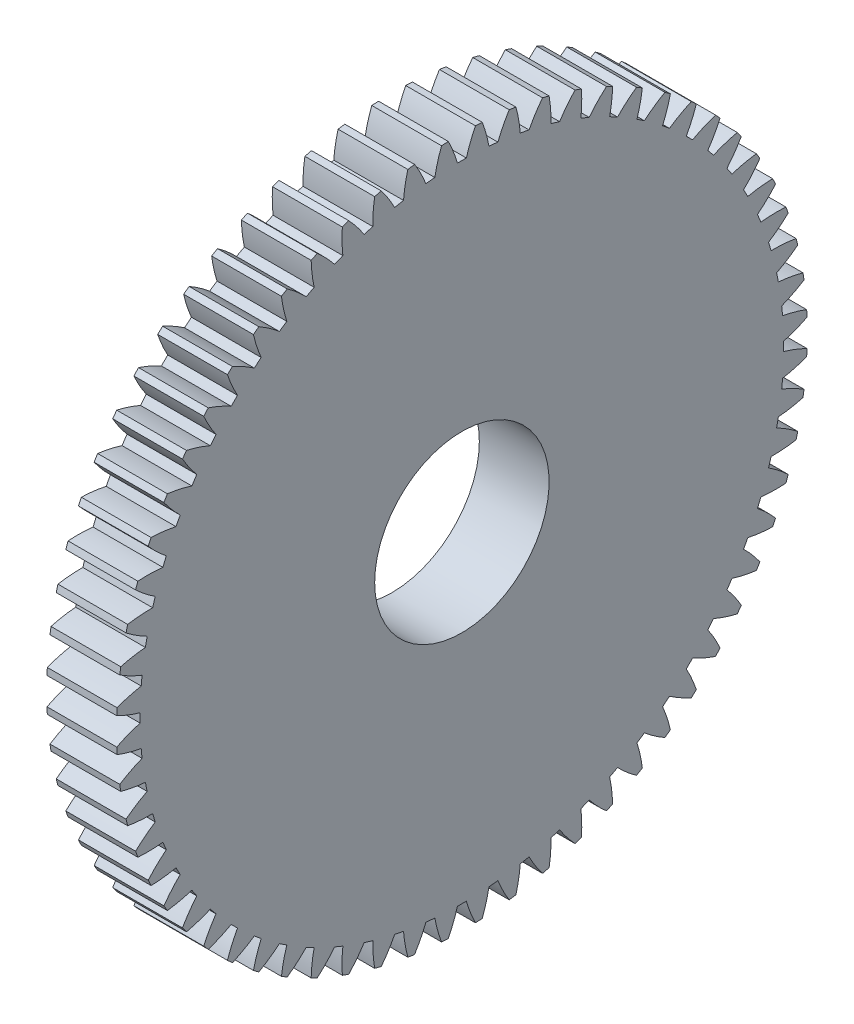
SolidWorks part; units mm, degrees
ref_plane "Plane1" through (0, 0, 0) normal (0, 0, 1) x (1, 0, 0)
ref_plane "Plane2" through (0, 0, 0) normal (0, 1, 0) x (1, 0, 0)
ref_plane "Plane3" through (0, 0, 0) normal (1, 0, 0) x (0, 0, -1)
sketch "HoldingSke" plane through (0, 0, 0) normal (0, 1, 0) x (1, 0, 0)
  line L0 (0, 0) -> (0.7306, -1.498)
  line L1 (-15, 0) -> (100, 0) construction
  line L2 (0, 0) -> (-2.1039, 2.3779)
  line L3 (0, 0) -> (-11.863, 4.5341)
  line L4 (0, 0) -> (3.7858, 7.762)
  line L5 (0, 0) -> (-46.8476, -17.4728)
  line L6 (0, 0) -> (-3.3159, -2.2372)
  line L7 (-2.1039, 2.3779) -> (8.6586, 51.2059)
  line L8 (-76.2, 54.61) -> (-74.4, 54.61)
  line L9 (-71.009, 38.7566) -> (-53.1078, 45.2721)
  line L10 (-76.2, 71.12) -> (104.1128, 71.12)
  line L11 (0, 0) -> (-4, 0)
  line L12 (-76.2, 101.6) -> (-76.177, 101.6)
  line L13 (24.9733, 27.94) -> (52.9518, 28.4284)
  line L14 (24.9733, 27.94) -> (24.9743, 27.94)
  line L15 (24.9733, 27.94) -> (100.4006, 29.5858)
  line L16 (-63.627, -0.6) -> (-12.827, -0.6)
  circle A0 centre (0, 0) radius 5
  circle A1 centre (0, 0) radius 18.449
  circle A2 centre (0, 0) radius 37.5
  circle A3 centre (0, 0) radius 5
  dimension "MHD" = 36.898
  dimension "Hub_dia" = 75
  dimension "Bore" = 10
  dimension "MBD" = 10
  dimension "Num_teeth" = 64
  dimension "Pitch" = 1.6667
  dimension "Overall_len" = 50
  dimension "Show_teeth" = 64
  dimension "Thickness" = 4
  dimension "OAL" = 50.0001
  dimension "T_dim" = 1.8
  dimension "Ap" = 20
  dimension "H" = 19.05
  dimension "Pitch_radius" = 180.3128
  dimension "Width" = 4
  dimension "Backlash" = 0.023
  dimension "Addendum_fac" = 1
  dimension "Dedendum_fac" = 1.25
  dimension "Clearance_fac" = 0.25
  dimension "Dedendum_add" = 0.001
  dimension "Module" = 0.6
sketch "BasProSke" plane through (0, 0, 0) normal (0, 1, 0) x (1, 0, 0)
  line L0 (-10, 0) -> (60, 0) construction
  line L1 (0, 0) -> (0, 19.8)
  line L2 (0, 0) -> (4, 0)
  line L3 (4, 0) -> (4, 19.8)
  line L4 (4, 19.8) -> (0, 19.8)
  dimension "Thickness" = 4
  dimension "Diameter" = 39.6
revolve "Base-Revolve" add sketch "BasProSke" angle 360 about L0
sketch "TooCutSke" plane through (0, 0, 0) normal (1, 0, 0) x (0, 0, -1)
  line L1 (0, 0) -> (0, 107) construction
  line L2 (0, 0) -> (-0.5114, 19.1932) construction
  line L3 (0, 0) -> (-1.8837, 38.3441) construction
  line L4 (-0.5114, 19.1932) -> (-0.9419, 19.172) construction
  arc A0 (0.2569, 18.4472) -> (-0.2569, 18.4472) centre (0, 0) ccw
  arc A1 (0.7899, 19.8097) -> (-0.7899, 19.8097) centre (0, 0) ccw
  circle A2 centre (0, 0) radius 19.2 construction
  circle A3 centre (0, 0) radius 18.0421 construction
  arc A4 (-0.2569, 18.4472) -> (-0.7899, 19.8097) centre (-7.6431, 16.3432) ccw
  arc A5 (0.7899, 19.8097) -> (0.2569, 18.4472) centre (7.6431, 16.3432) ccw
  dimension "Root_dia" = 36.898
  dimension "Overcut_dia" = 39.6508
  dimension "Pitch_dia" = 38.4
  dimension "Base_dia" = 36.0842
  dimension "Flank_rad" = 7.68
  dimension "Half_ang" = 2.813
  dimension "Half_CT" = 0.4309
extrude "ToothCut" cut sketch "TooCutSke" along normal through all
fillet "Breaks" [suppressed] radius 0.012
fillet "RootFillets" [suppressed] radius 0.151
pattern_circular "TeethCuts" count 64 every 5.625 about axis through (-10, 0, 0) along (1, 0, 0) of "ToothCut", "RootFillets", "Breaks"
sketch "HubNeaOneSke" plane through (0, 0, 0) normal (-1, 0, 0) x (0, 0, 1)
  circle A0 centre (0, 0) radius 18.449
  dimension "Diameter" = 36.898
extrude "HubNearOne" [suppressed] add sketch "HubNeaOneSke" along normal blind 46.0001
sketch "HubNeaBotSke" plane through (0, 0, 0) normal (-1, 0, 0) x (0, 0, 1)
  circle A0 centre (0, 0) radius 18.449
  dimension "Diameter" = 36.898
extrude "HubNearBoth" [suppressed] add sketch "HubNeaBotSke" along normal blind 23
ref_plane "FarPln" through (4, 0, 0) normal (1, 0, 0) x (0, 0, -1)
sketch "HubFarSke" plane through (4, 0, 0) normal (1, 0, 0) x (0, 0, -1)
  circle A0 centre (0, 0) radius 18.449
  dimension "Diameter" = 36.898
extrude "HubFar" [suppressed] add sketch "HubFarSke" along normal blind 23
sketch "BorSke" plane through (0, 0, 0) normal (1, 0, 0) x (0, 0, -1)
  circle A0 centre (0, 0) radius 5
  dimension "Diameter" = 10
extrude "Bore" cut sketch "BorSke" along normal mid plane 100.0001
sketch "KeySke" plane through (0, 0, 0) normal (1, 0, 0) x (0, 0, -1)
  line L0 (-2, 0) -> (-2, 6.8)
  line L1 (-2, 6.8) -> (2, 6.8)
  line L2 (2, 6.8) -> (2, 0)
  line L3 (0, 0) -> (0, 34) construction
  line L4 (-2, 0) -> (2, 0)
  dimension "Width" = 4
  dimension "Offset" = 6.8
extrude "Keyway" [suppressed] cut sketch "KeySke" along normal mid plane 100.0001
pattern_circular "Keyway2" [suppressed] count 2 every 90 about axis through (-10, 0, 0) along (1, 0, 0)
equation "' \"Module@HoldingSke\" = 6.35"
equation "' \"Num_teeth@HoldingSke\" = 12"
equation "' \"Ap@HoldingSke\" =  20"
equation "' \"Ap@HoldingSke\" = 20"
equation "' \"Width@HoldingSke\" = 0.5 * 25.4"
equation "' \"Hub_dia@HoldingSke\"= 1 * 25.4"
equation "' \"Hub_dia@HoldingSke\" = 1 * 25.4"
equation "' \"Overall_len@HoldingSke\" = 1.0 * 25.4"
equation "' \"Bore@HoldingSke\" = 0.75 * 25.4"
equation "' \"T_dim@HoldingSke\" = 0.1 * 25.4"
equation "' \"Width@KeySke\" = 0.25 * 25.4"
equation "' \"Show_teeth@HoldingSke\" = 13"
equation "' \"Backlash@HoldingSke\" = 0.009 * 25.4"
equation "' \"Addendum_fac@HoldingSke\" = 1.0"
equation "' \"Dedendum_fac@HoldingSke\" = 1.25"
equation "' \"Dedendum_add@HoldingSke\" = 0.00005 * 25.4"
equation "' \"Clearance_fac@HoldingSke\" = 0.25"
equation "\"Pitch@HoldingSke\" = 1 / \"Module@HoldingSke\""
equation "\"Overcut_dia@TooCutSke\" = (\"Num_teeth@HoldingSke\" + 2 * \"Addendum_fac@HoldingSke\") / \"Pitch@HoldingSke\" + 0.002 * 25.4"
equation "\"Pitch_dia@TooCutSke\" = \"Num_teeth@HoldingSke\" / \"Pitch@HoldingSke\""
equation "\"Base_dia@TooCutSke\" = \"Num_teeth@HoldingSke\" / \"Pitch@HoldingSke\" * cos((\"Ap@HoldingSke\"  * 3.14159265 / 180))"
equation "\"Root_dia@TooCutSke\" = (\"Num_teeth@HoldingSke\" + 2) / \"Pitch@HoldingSke\" - 2 * (\"Addendum_fac@HoldingSke\" + \"Dedendum_fac@HoldingSke\") / \"Pitch@HoldingSke\" - \"Dedendum_add@HoldingSke\" * 2"
equation "\"Half_ang@TooCutSke\" = 180 / \"Num_teeth@HoldingSke\""
equation "\"Half_CT@TooCutSke\" = \"Num_teeth@HoldingSke\" / \"Pitch@HoldingSke\" * sin((3.14159265 / 2 / \"Num_teeth@HoldingSke\")) / 2 - 7 * \"Backlash@HoldingSke\" / 4"
equation "\"Flank_rad@TooCutSke\" = \"Num_teeth@HoldingSke\" / \"Pitch@HoldingSke\" / 5"
equation "\"Radius@RootFillets\" = \"Clearance_fac@HoldingSke\" / \"Pitch@HoldingSke\" + \"Dedendum_add@HoldingSke\""
equation "\"Break_rad@Breaks\" = 0.02 / \"Pitch@HoldingSke\""
equation "\"Thickness@HoldingSke\" = \"Width@HoldingSke\""
equation "\"OAL@HoldingSke\" = \"Thickness@HoldingSke\""
equation "\"MHD@HoldingSke\" = (\"Num_teeth@HoldingSke\" + 2) / \"Pitch@HoldingSke\" - 2 * (\"Addendum_fac@HoldingSke\" + \"Dedendum_fac@HoldingSke\")  / \"Pitch@HoldingSke\" - \"Dedendum_add@HoldingSke\" * 2"
equation "\"MBD@HoldingSke\" = (\"Num_teeth@HoldingSke\" + 2) / \"Pitch@HoldingSke\" - 2 * (\"Addendum_fac@HoldingSke\" + \"Dedendum_fac@HoldingSke\")  / \"Pitch@HoldingSke\" - \"Dedendum_add@HoldingSke\" * 2 - 0.002 * 25.4"
equation "\"MHD@HoldingSke\" = ((sgn( \"MHD@HoldingSke\" - \"Hub_dia@HoldingSke\" )-1)*( \"MHD@HoldingSke\" - \"Hub_dia@HoldingSke\" ))/-2+ \"Hub_dia@HoldingSke\""
equation "\"MBD@HoldingSke\" = ((sgn( \"MBD@HoldingSke\" - \"Bore@HoldingSke\" )-1)*( \"MBD@HoldingSke\" - \"Bore@HoldingSke\" ))/-2+ \"Bore@HoldingSke\""
equation "\"OAL@HoldingSke\" = ((sgn( \"OAL@HoldingSke\" - \"Overall_len@HoldingSke\" )+1)*( \"OAL@HoldingSke\" - \"Overall_len@HoldingSke\" ))/2 + \"Overall_len@HoldingSke\" + 0.000002 * 25.4"
equation "\"Num_teeth@TeethCuts\" = int( \"Show_teeth@HoldingSke\" ) + 1"
equation "\"Num_teeth@TeethCuts\" = ((sgn( \"Num_teeth@TeethCuts\" - \"Num_teeth@HoldingSke\" )-1)*( \"Num_teeth@TeethCuts\" - \"Num_teeth@HoldingSke\" ))/-2+ \"Num_teeth@HoldingSke\""
equation "\"Num_teeth@TeethCuts\" = ((sgn( \"Num_teeth@TeethCuts\" - 2.0)+1)*( \"Num_teeth@TeethCuts\" - 2.0))/2 +2.0"
equation "\"Angle@TeethCuts\" = 360.0 / \"Num_teeth@HoldingSke\""
equation "\"Diameter@BasProSke\" = (\"Num_teeth@HoldingSke\" + 2 * \"Addendum_fac@HoldingSke\") / \"Pitch@HoldingSke\""
equation "\"Thickness@BasProSke\"  = \"Thickness@HoldingSke\""
equation "' \"Fillet_rad@BasProSke\" =  \"Thickness@HoldingSke\" * 0.05"
equation "' \"Fillet_rad@BasProSke\" = \"Thickness@HoldingSke\" * 0.05"
equation "\"MHD@HoldingSke\" = ((sgn( \"MHD@HoldingSke\" - \"Root_dia@TooCutSke\" )-1)*( \"MHD@HoldingSke\" - \"Root_dia@TooCutSke\" ))/-2+ \"Root_dia@TooCutSke\""
equation "\"Diameter@HubNeaOneSke\" = \"MHD@HoldingSke\""
equation "\"Length@HubNearOne\" = \"OAL@HoldingSke\" - \"Thickness@BasProSke\""
equation "\"Diameter@HubNeaBotSke\" = \"MHD@HoldingSke\""
equation "\"Length@HubNearBoth\" = ( \"OAL@HoldingSke\" - \"Thickness@BasProSke\" ) / 2.0"
equation "\"Thickness@FarPln\" = \"Thickness@BasProSke\""
equation "\"Diameter@HubFarSke\" = \"MHD@HoldingSke\""
equation "\"Length@HubFar\" = ( \"OAL@HoldingSke\" - \"Thickness@BasProSke\" ) / 2.0"
equation "\"Diameter@BorSke\" = \"MBD@HoldingSke\""
equation "\"D1@Bore\" = \"OAL@HoldingSke\" * 2.0"
equation "\"D1@Keyway\" = \"OAL@HoldingSke\" * 2.0"
equation "\"Offset@KeySke\" = \"T_dim@HoldingSke\" + \"MBD@HoldingSke\" / 2.0"
